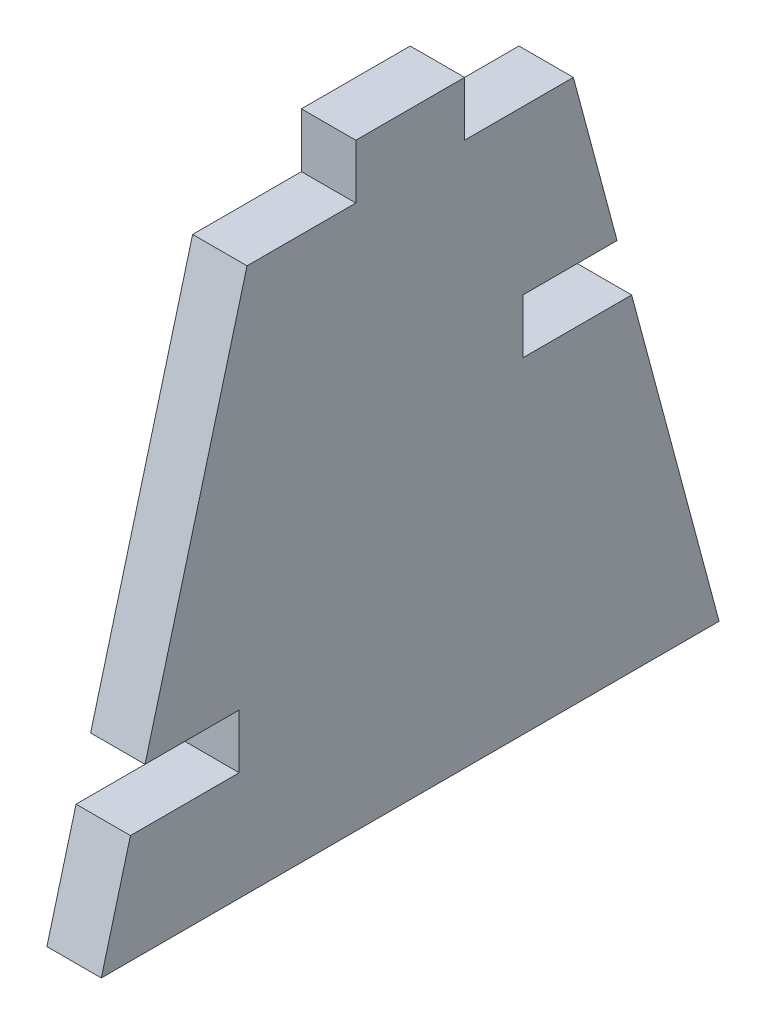
SolidWorks part; units mm, degrees
ref_plane "Front Plane" through (0, 0, 0) normal (0, 0, 1) x (1, 0, 0)
ref_plane "Top Plane" through (0, 0, 0) normal (0, 1, 0) x (1, 0, 0)
ref_plane "Right Plane" through (0, 0, 0) normal (1, 0, 0) x (0, 0, -1)
sketch "Sketch1" plane through (0, 0, 0) normal (1, 0, 0) x (0, 0, -1)
  line L0 (0, 0) -> (113.5898, 0)
  line L1 (56.7949, -32.6537) -> (56.7949, 127.3278) construction
  line L2 (-21.1845, 100) -> (134.7743, 100) construction
  line L3 (26.7949, 100) -> (46.7949, 100)
  line L4 (26.7949, 100) -> (8.0385, 30)
  line L5 (86.7949, 100) -> (94.8334, 70)
  line L6 (-21.1845, 0) -> (-21.1845, 20) construction
  line L7 (5.359, 20) -> (25.359, 20)
  line L8 (25.359, 20) -> (25.359, 30)
  line L9 (25.359, 30) -> (8.0385, 30)
  line L10 (133.0246, 0) -> (133.0246, 60) construction
  line L11 (97.5129, 60) -> (77.5129, 60)
  line L12 (77.5129, 60) -> (77.5129, 70)
  line L13 (77.5129, 70) -> (94.8334, 70)
  line L14 (66.7949, 110) -> (46.7949, 110)
  line L15 (66.7949, 110) -> (66.7949, 100)
  line L16 (46.7949, 110) -> (46.7949, 100)
  line L17 (66.7949, 100) -> (86.7949, 100)
  line L18 (97.5129, 60) -> (113.5898, 0)
  line L19 (5.359, 20) -> (0, 0)
  point P8 (56.7949, 100)
  point P11 (56.7949, 100)
  point P26 (56.7949, 110)
  dimension "D1" = 75
  dimension "D2" = 20
  dimension "D3" = 60
  dimension "D4" = 60
  dimension "D5" = 75
  dimension "D7" = 100
extrude "Boss-Extrude1" add sketch "Sketch1" against normal blind 10 contours L4 L9 L8 L7 L19 L0 L18 L11 L12 L13 L5 L17 L15 L14 L16 L3
